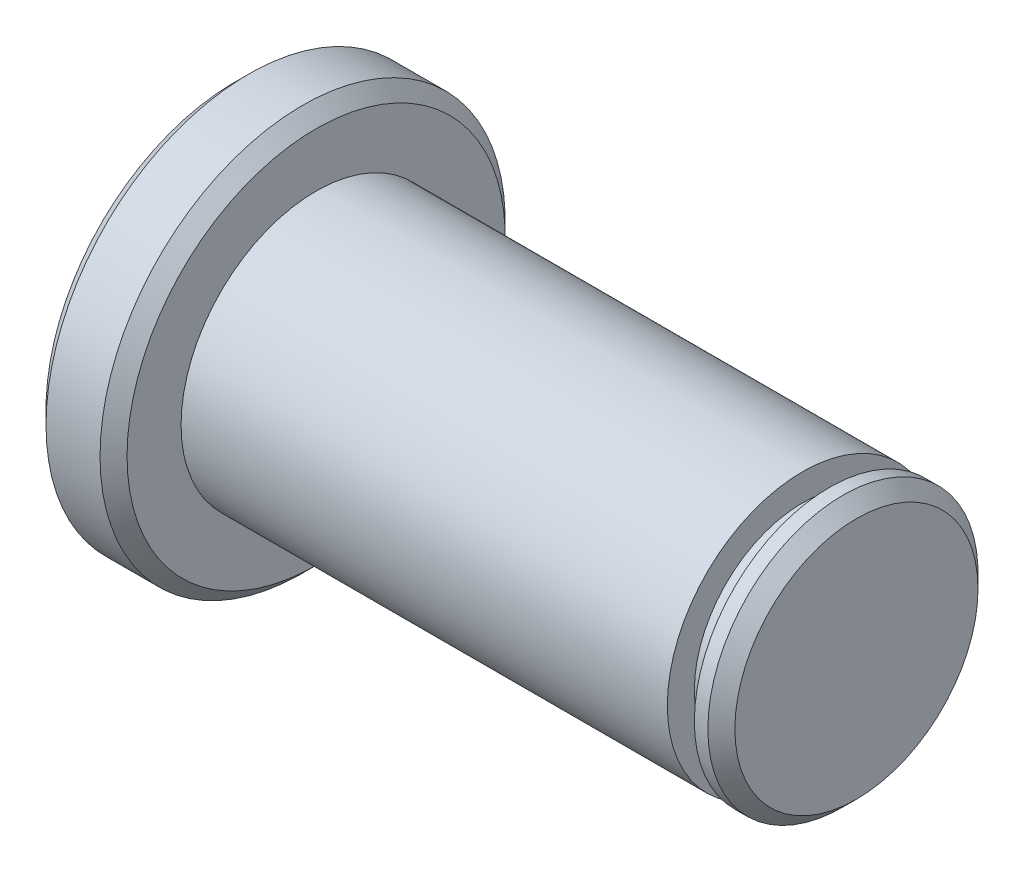
SolidWorks part; units mm, degrees
ref_plane "前视基准面" through (0, 0, 0) normal (0, 0, 1) x (1, 0, 0)
ref_plane "上视基准面" through (0, 0, 0) normal (0, 1, 0) x (1, 0, 0)
ref_plane "右视基准面" through (0, 0, 0) normal (1, 0, 0) x (0, 0, -1)
sketch "草图1" plane through (0, 0, 0) normal (0, 0, 1) x (1, 0, 0)
  line L0 (-11.6304, 0) -> (18.8307, 0) construction
  line L1 (-6.2319, 0) -> (-6.2319, 7.5)
  line L2 (-6.2319, 7.5) -> (-3.2319, 7.5)
  line L3 (-3.2319, 7.5) -> (-3.2319, 5)
  line L4 (-3.2319, 5) -> (14.7681, 5)
  line L5 (14.7681, 5) -> (14.7681, 4)
  line L6 (14.7681, 4) -> (15.7681, 4)
  line L7 (15.7681, 4) -> (15.7681, 5)
  line L8 (15.7681, 5) -> (16.7681, 5)
  line L9 (16.7681, 5) -> (16.7681, 0)
  line L10 (16.7681, 0) -> (-6.2319, 0)
  dimension "D1" = 7.5
  dimension "D2" = 18
  dimension "D3" = 23
  dimension "D4" = 2
  dimension "D5" = 1
  dimension "D6" = 5
  dimension "D7" = 5
  dimension "D8" = 1
revolve "旋转1" add sketch "草图1" angle 360 about L0
chamfer "倒角1" distance 0.5 angle 45 3 edges at (16.7681, 0, 5) (-3.2319, 0, 7.5) (-6.2319, 0, 7.5)
